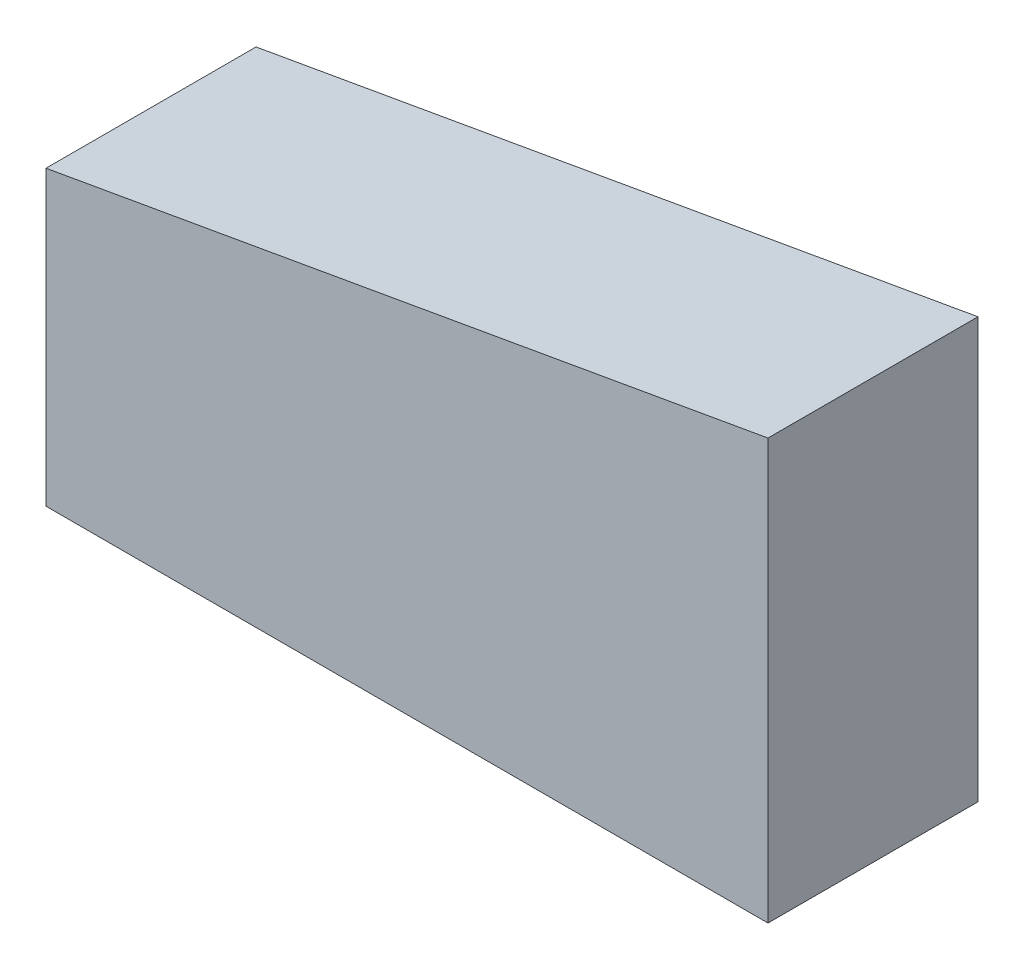
SolidWorks part; units mm, degrees
ref_plane "Plan de face" through (0, 0, 0) normal (0, 0, 1) x (1, 0, 0)
ref_plane "Plan de dessus" through (0, 0, 0) normal (0, 1, 0) x (1, 0, 0)
ref_plane "Plan de droite" through (0, 0, 0) normal (1, 0, 0) x (0, 0, -1)
sketch "Esquisse1" plane through (0, 0, 0) normal (0, 0, 1) x (1, 0, 0)
  line L0 (0, 0) -> (-55, 0)
  line L1 (-55, 0) -> (-55, 22.302)
  line L2 (-55, 22.302) -> (0, 32)
  line L3 (0, 32) -> (0, 0)
  dimension "D1" = 32
  dimension "D2" = 55
  dimension "D3" = 80
extrude "Boss.-Extru.1" add sketch "Esquisse1" along normal blind 16
